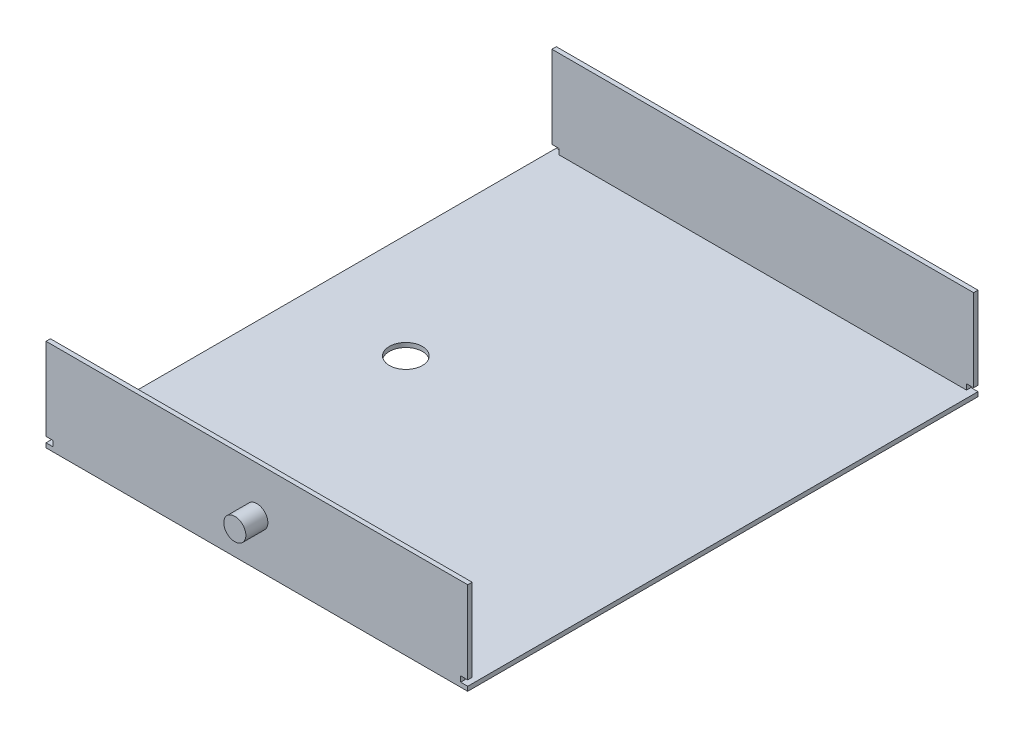
SolidWorks part; units mm, degrees
ref_plane "Front Plane" through (0, 0, 0) normal (0, 0, 1) x (1, 0, 0)
ref_plane "Top Plane" through (0, 0, 0) normal (0, 1, 0) x (1, 0, 0)
ref_plane "Right Plane" through (0, 0, 0) normal (1, 0, 0) x (0, 0, -1)
sketch "草图2" plane through (0, 0, 0) normal (0, 1, 0) x (1, 0, 0)
  line L1 (95.7, -115.8) -> (-95.7, -115.8)
  line L2 (95.7, -115.8) -> (95.7, 115.8)
  line L3 (95.7, 115.8) -> (-95.7, 115.8)
  line L4 (-95.7, -115.8) -> (-95.7, 115.8)
  line L5 (95.7, -115.8) -> (-95.7, 115.8) construction
  line L6 (95.7, 115.8) -> (-95.7, -115.8) construction
  point P0 (0, 0)
  dimension "D1" = 231.6
  dimension "D2" = 191.4
extrude "凸台-拉伸1" add sketch "草图2" along normal blind 2
sketch "草图3" plane through (0, 2, 0) normal (0, 1, 0) x (1, 0, 0)
  line L0 (95.7, 115.8) -> (-95.7, 115.8) construction
  line L1 (-92.5, 115.8) -> (92.5, 115.8)
  line L2 (-92.5, 115.8) -> (-92.5, 113.8)
  line L3 (-92.5, 113.8) -> (92.5, 113.8)
  line L4 (92.5, 115.8) -> (92.5, 113.8)
  line L5 (-95.7, 115.8) -> (-95.7, -115.8) construction
  line L6 (95.7, -115.8) -> (95.7, 115.8) construction
  line L8 (-92.5, -113.8) -> (92.5, -113.8)
  line L9 (92.5, -115.8) -> (92.5, -113.8)
  line L10 (-92.5, -115.8) -> (92.5, -115.8)
  line L11 (-92.5, -115.8) -> (-92.5, -113.8)
  dimension "D1" = 3.2
  dimension "D2" = 3.2
  dimension "D3" = 2
extrude "凸台-拉伸2" add sketch "草图3" along normal blind 2.5
sketch "草图4" plane through (0, 4.5, 0) normal (0, 1, 0) x (1, 0, 0)
  line L0 (92.5, 115.8) -> (-92.5, 115.8) construction
  line L1 (-95.7, 115.8) -> (95.7, 115.8)
  line L2 (-95.7, 115.8) -> (-95.7, 113.8)
  line L3 (-95.7, 113.8) -> (95.7, 113.8)
  line L4 (95.7, 115.8) -> (95.7, 113.8)
  line L5 (-92.5, 113.8) -> (92.5, 113.8) construction
  line L7 (95.7, -115.8) -> (95.7, 115.8) construction
  line L9 (-95.7, -113.8) -> (95.7, -113.8)
  line L10 (95.7, -115.8) -> (95.7, -113.8)
  line L11 (-95.7, -115.8) -> (95.7, -115.8)
  line L12 (-95.7, -115.8) -> (-95.7, -113.8)
extrude "凸台-拉伸3" add sketch "草图4" along normal blind 37.4
sketch "草图7" plane through (0, 0, 115.8) normal (0, 0, 1) x (1, 0, 0)
  circle A0 centre (0, 20.95) radius 5
  dimension "D1" = 10
extrude "凸台-拉伸5" add sketch "草图7" along normal blind 10
sketch "Sketch1" plane through (0, 0, 0) normal (0, -1, 0) x (1, 0, 0)
  circle A0 centre (-48.1707, 0) radius 7.5
  point P2 (-48.1707, 0)
  dimension "D1" = 15
extrude "Cut-Extrude1" cut sketch "Sketch1" against normal blind 10
